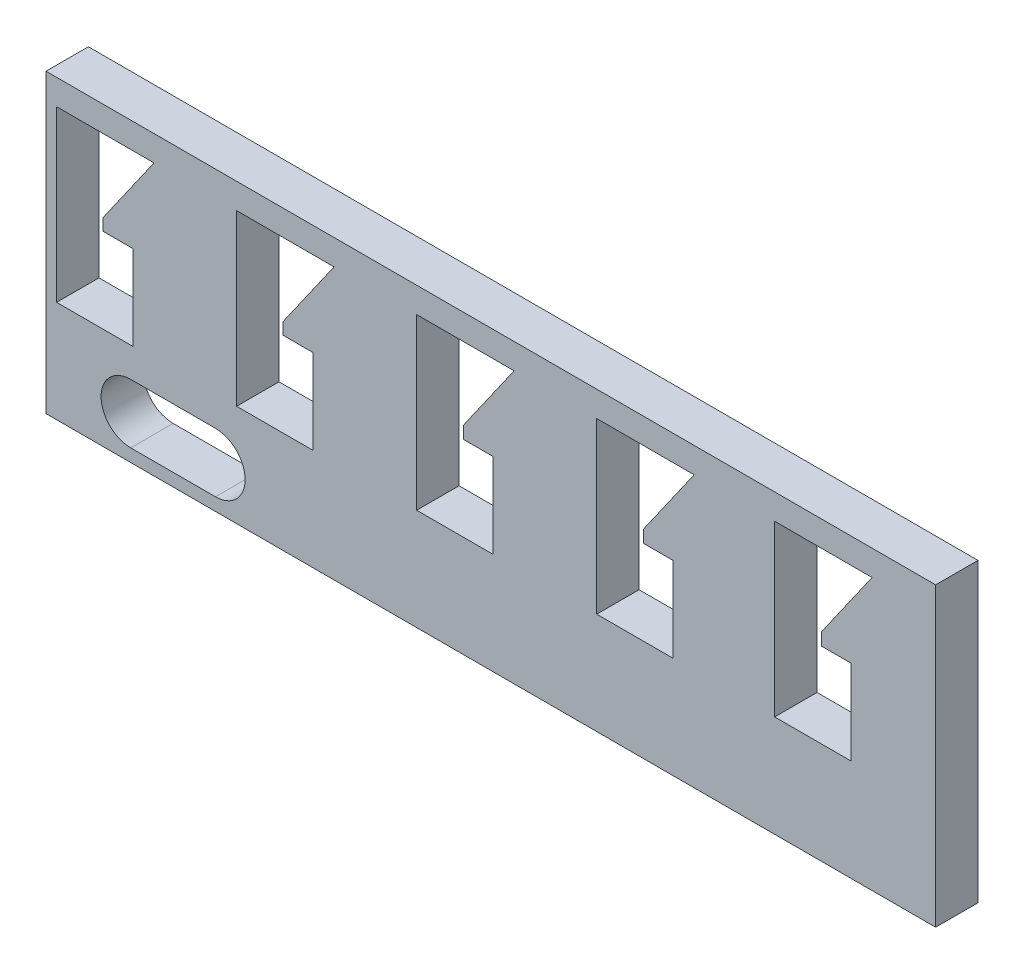
SolidWorks part; units mm, degrees
ref_plane "Front Plane" through (0, 0, 0) normal (0, 0, 1) x (1, 0, 0)
ref_plane "Top Plane" through (0, 0, 0) normal (0, 1, 0) x (1, 0, 0)
ref_plane "Right Plane" through (0, 0, 0) normal (1, 0, 0) x (0, 0, -1)
sketch "Sketch1" plane through (0, 0, 0) normal (0, 0, 1) x (1, 0, 0)
  line L1 (-44.8, 23.1) -> (60.2, 23.1)
  line L2 (-44.8, 23.1) -> (-44.8, -11.9)
  line L3 (-44.8, -11.9) -> (60.2, -11.9)
  line L4 (60.2, 23.1) -> (60.2, -11.9)
  dimension "D1" = 105
  dimension "D2" = 35
extrude "Boss-Extrude1" add sketch "Sketch1" along normal blind 5
sketch "Sketch2" plane through (0, 0, 5) normal (0, 0, 1) x (1, 0, 0)
  line L0 (-44.8, 23.1) -> (-44.8, -11.9) construction
  line L1 (-44.8, -11.9) -> (60.2, -11.9) construction
  line L2 (-34.8, -3.4) -> (-24.8, -3.4)
  line L3 (-24.8, -10.4) -> (-34.8, -10.4)
  arc A0 (-34.8, -3.4) -> (-34.8, -10.4) centre (-34.8, -6.9) ccw
  arc A1 (-24.8, -10.4) -> (-24.8, -3.4) centre (-24.8, -6.9) ccw
  dimension "D2" = 7
  dimension "D4" = 7
  dimension "D1" = 10
  dimension "D3" = 5
  dimension "D5" = 10
extrude "Cut-Extrude1" cut sketch "Sketch2" against normal blind 5
sketch "Sketch3" plane through (0, 0, 0) normal (0, 0, -1) x (-1, 0, 0)
  line L0 (44.8, -11.9) -> (-60.2, -11.9) construction
  circle A0 centre (8.8, -6.9) radius 2.5
  arc A1 (24.8, -3.4) -> (24.8, -10.4) centre (24.8, -6.9) ccw construction
  point P8 (21.3, -6.9)
  dimension "D1" = 5
  dimension "D2" = 5
  dimension "D3" = 12.5
extrude "Boss-Extrude2" add sketch "Sketch3" along normal blind 5
sketch "Sketch4" plane through (0, 0, -5) normal (0, 0, -1) x (-1, 0, 0)
  circle A0 centre (8.8, -6.9) radius 2.5
  circle A1 centre (8.8, -6.9) radius 1.5
  dimension "D1" = 3
extrude "Cut-Extrude3" cut sketch "Sketch4" against normal blind 1.5 from offset 2 offset against normal yes
sketch "Sketch5" plane through (0, 0, 0) normal (0, 0, -1) x (-1, 0, 0)
  line L0 (-60.2, -11.9) -> (-60.2, 23.1) construction
  line L1 (-41.2, 0.1) -> (-50.2, 0.1)
  line L2 (-41.2, 0.1) -> (-41.2, 20.1)
  line L3 (-41.2, 20.1) -> (-52.7, 20.1)
  line L6 (-50.2, 0.1) -> (-50.2, 10.1)
  line L9 (-20.2, 0.1) -> (-29.2, 0.1)
  line L10 (-52.7, 20.1) -> (-45.7, 10.1)
  line L11 (-45.7, 10.1) -> (-50.2, 10.1)
  line L12 (-20.2, 0.1) -> (-20.2, 20.1)
  line L13 (-20.2, 20.1) -> (-31.7, 20.1)
  line L14 (-29.2, 0.1) -> (-29.2, 10.1)
  line L15 (-31.7, 20.1) -> (-24.7, 10.1)
  line L16 (-24.7, 10.1) -> (-29.2, 10.1)
  line L17 (-60.2, 23.1) -> (44.8, 23.1) construction
  line L18 (1.05, 0.1) -> (-7.95, 0.1)
  line L19 (1.05, 0.1) -> (1.05, 20.1)
  line L20 (1.05, 20.1) -> (-10.45, 20.1)
  line L21 (-7.95, 0.1) -> (-7.95, 10.1)
  line L22 (-10.45, 20.1) -> (-3.45, 10.1)
  line L23 (-3.45, 10.1) -> (-7.95, 10.1)
  line L24 (22.3, 0.1) -> (13.3, 0.1)
  line L25 (22.3, 0.1) -> (22.3, 20.1)
  line L26 (22.3, 20.1) -> (10.8, 20.1)
  line L27 (13.3, 0.1) -> (13.3, 10.1)
  line L28 (10.8, 20.1) -> (17.8, 10.1)
  line L29 (17.8, 10.1) -> (13.3, 10.1)
  line L30 (43.55, 0.1) -> (34.55, 0.1)
  line L31 (43.55, 0.1) -> (43.55, 20.1)
  line L32 (43.55, 20.1) -> (32.05, 20.1)
  line L33 (34.55, 0.1) -> (34.55, 10.1)
  line L34 (32.05, 20.1) -> (39.05, 10.1)
  line L35 (39.05, 10.1) -> (34.55, 10.1)
  dimension "D1" = 11.5
  dimension "D2" = 20
  dimension "D3" = 10
  dimension "D4" = 4.5
  dimension "D5" = 9
  dimension "D6" = 10
  dimension "D7" = 11.5
  dimension "D8" = 20
  dimension "D9" = 10
  dimension "D10" = 4.5
  dimension "D11" = 9
  dimension "D12" = 31
  dimension "D13" = 3
  dimension "D14" = 3
  dimension "D15" = 11.5
  dimension "D16" = 20
  dimension "D17" = 10
  dimension "D18" = 4.5
  dimension "D19" = 9
  dimension "D20" = 3
  dimension "D21" = 21.25
  dimension "D22" = 11.5
  dimension "D23" = 20
  dimension "D24" = 10
  dimension "D25" = 4.5
  dimension "D26" = 9
  dimension "D27" = 3
  dimension "D28" = 21.25
  dimension "D29" = 11.5
  dimension "D30" = 20
  dimension "D31" = 10
  dimension "D32" = 4.5
  dimension "D33" = 9
  dimension "D34" = 3
  dimension "D35" = 21.25
extrude "Cut-Extrude4" cut sketch "Sketch5" against normal blind 5
sketch "Sketch6" plane through (0, 0, 0) normal (0, 0, -1) x (-1, 0, 0)
  line L0 (-35.7, 28.2156) -> (-35.7, -14.6963) construction
  line L1 (-45.7, 13.2818) -> (-46.7, 13.2818)
  line L2 (-45.7, 13.2818) -> (-45.7, 7.8084)
  line L3 (-45.7, 7.8084) -> (-46.7, 7.8084)
  line L4 (-46.7, 13.2818) -> (-46.7, 7.8084)
  line L6 (-24.7, 13.2818) -> (-24.7, 7.8084)
  line L7 (-25.7, 7.8084) -> (-24.7, 7.8084)
  line L8 (-25.7, 13.2818) -> (-25.7, 7.8084)
  line L9 (-25.7, 13.2818) -> (-24.7, 13.2818)
  line L10 (-4.45, 12.0802) -> (-3.45, 12.0802)
  line L11 (-4.45, 12.0802) -> (-4.45, 9.2295)
  line L12 (-4.45, 9.2295) -> (-3.45, 9.2295)
  line L13 (-3.45, 12.0802) -> (-3.45, 9.2295)
  line L14 (16.8, 13.2818) -> (17.8, 13.2818)
  line L15 (16.8, 13.2818) -> (16.8, 8.6398)
  line L16 (16.8, 8.6398) -> (17.8, 8.6398)
  line L17 (17.8, 13.2818) -> (17.8, 8.6398)
  line L18 (38.05, 12.4237) -> (39.05, 12.4237)
  line L19 (38.05, 12.4237) -> (38.05, 9.2295)
  line L20 (38.05, 9.2295) -> (39.05, 9.2295)
  line L21 (39.05, 12.4237) -> (39.05, 9.2295)
  dimension "D1" = 0
  dimension "D2" = 1
  dimension "D3" = 11
  dimension "D4" = 1
  dimension "D5" = 0
  dimension "D6" = 0
  dimension "D7" = 1
  dimension "D8" = 0
  dimension "D9" = 1
extrude "Cut-Extrude5" cut sketch "Sketch6" against normal blind 10
